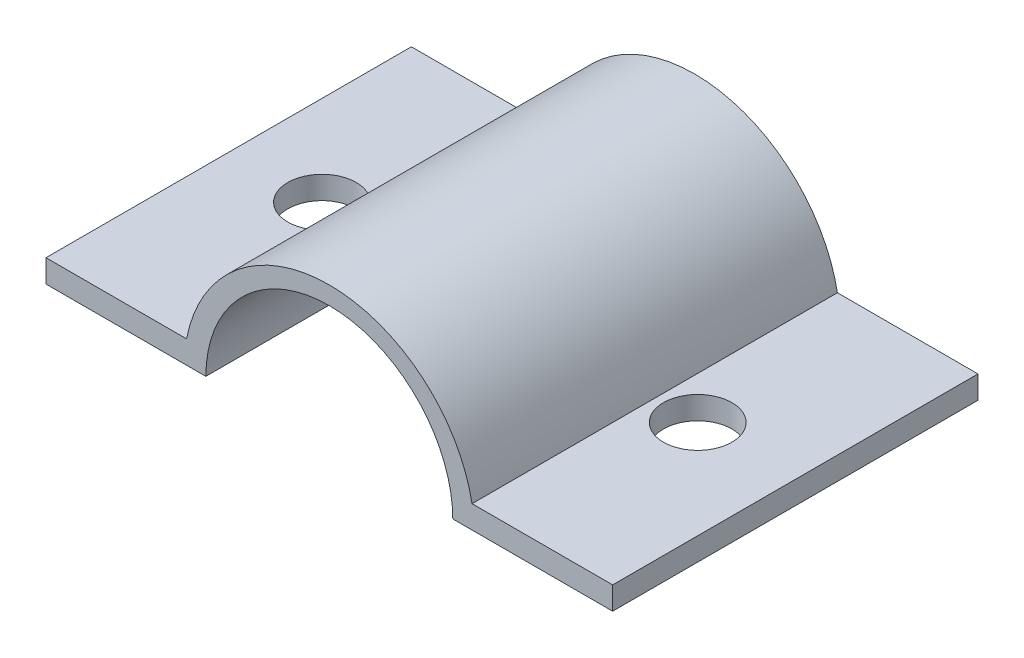
SolidWorks part; units mm, degrees
ref_plane "Front Plane" through (0, 0, 0) normal (0, 0, 1) x (1, 0, 0)
ref_plane "Top Plane" through (0, 0, 0) normal (0, 1, 0) x (1, 0, 0)
ref_plane "Right Plane" through (0, 0, 0) normal (1, 0, 0) x (0, 0, -1)
sketch "Sketch5" plane through (0, 0, 0) normal (0, 0, 1) x (1, 0, 0)
  line L0 (-5.1439, 0) -> (8.8561, 0) construction
  line L1 (-3.6156, 0) -> (-10.6156, 0)
  line L2 (7.1994, 0) -> (14.1994, 0)
  line L3 (14.1994, 0) -> (14.1994, 1)
  line L4 (14.1994, 1) -> (8.0421, 1)
  line L5 (-10.6156, 0) -> (-10.6156, 1)
  line L6 (-10.6156, 1) -> (-4.4583, 1)
  line L9 (1.7919, -0.19) -> (1.7919, 5.31) construction
  arc A3 (-4.4583, 1) -> (8.0421, 1) centre (1.7919, -0.19) cw
  arc A4 (-3.6156, 0) -> (7.1994, 0) centre (1.7919, -0.0213) cw
  dimension "D7" = 5.5
  dimension "D1" = 14
  dimension "D2" = 7
  dimension "D3" = 7
  dimension "D6" = 1
  dimension "D9" = 1
extrude "Boss-Extrude3" add sketch "Sketch5" along normal blind 16
sketch "Sketch6" plane through (0, 1, 0) normal (0, 1, 0) x (1, 0, 0)
  line L0 (-5.1429, -7.7787) -> (8.8571, -7.7787) construction
  line L1 (-3.4953, -16) -> (-3.4953, -7.9754) construction
  line L2 (-4.4583, -16) -> (8.0421, -16) construction
  circle A0 centre (-6.6752, -7.8525) radius 1.5
  circle A1 centre (9.9005, -7.977) radius 1.5
  dimension "D1" = 3
  dimension "D2" = 14
extrude "Cut-Extrude3" cut sketch "Sketch6" against normal blind 6
